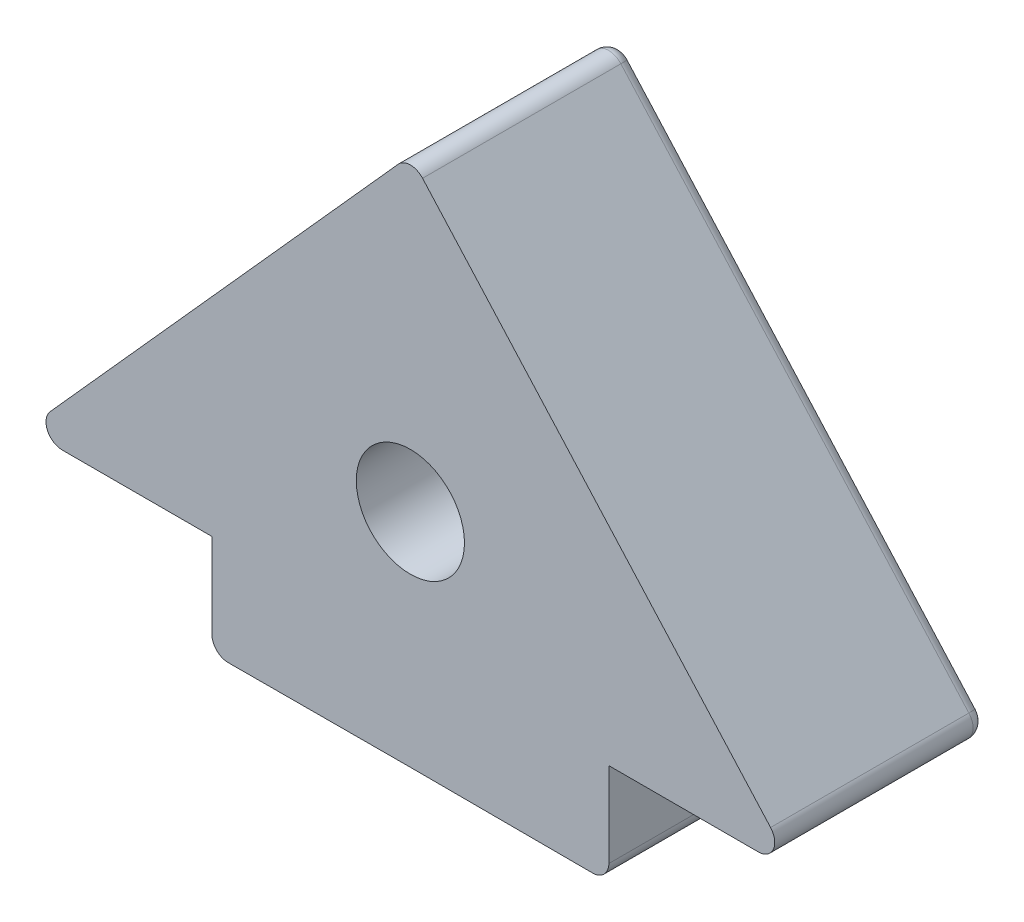
SolidWorks part; units mm, degrees
ref_plane "前视基准面" through (0, 0, 0) normal (0, 0, 1) x (1, 0, 0)
ref_plane "上视基准面" through (0, 0, 0) normal (0, 1, 0) x (1, 0, 0)
ref_plane "右视基准面" through (0, 0, 0) normal (1, 0, 0) x (0, 0, -1)
sketch "草图1" plane through (0, 0, 0) normal (0, 0, 1) x (1, 0, 0)
  line L0 (-0.7032, 8.7731) -> (-12.2849, -4.1469) construction
  line L1 (-11.5817, -5.7217) -> (-7.0052, -5.7217) construction
  line L2 (-7.0052, -5.7217) -> (-7.0052, -8.1427) construction
  line L3 (-6.0585, -9.0871) -> (0, -9.0721) construction
  line L4 (6.0585, -9.0871) -> (0, -9.0721) construction
  line L5 (7.0052, -5.7217) -> (7.0052, -8.1427) construction
  line L6 (11.5817, -5.7217) -> (7.0052, -5.7217) construction
  line L7 (0.7032, 8.7731) -> (12.2849, -4.1469) construction
  line L8 (-0.4054, 8.5061) -> (-11.9871, -4.4139)
  line L9 (-11.5817, -5.3217) -> (-6.6052, -5.3217)
  line L10 (-6.6052, -5.3217) -> (-6.6052, -8.1427)
  line L11 (-6.0595, -8.6871) -> (0, -8.6721)
  line L12 (6.0595, -8.6871) -> (0, -8.6721)
  line L13 (6.6052, -5.3217) -> (6.6052, -8.1427)
  line L14 (11.5817, -5.3217) -> (6.6052, -5.3217)
  line L15 (0.4054, 8.5061) -> (11.9871, -4.4139)
  line L16 (-0.7032, 8.7731) -> (-12.2849, -4.1469) construction
  line L17 (-11.5817, -5.7217) -> (-7.0052, -5.7217) construction
  line L18 (-7.0052, -5.7217) -> (-7.0052, -8.1427) construction
  line L19 (-6.0585, -9.0871) -> (0, -9.0721) construction
  line L20 (6.0585, -9.0871) -> (0, -9.0721) construction
  line L21 (7.0052, -5.7217) -> (7.0052, -8.1427) construction
  line L22 (11.5817, -5.7217) -> (7.0052, -5.7217) construction
  line L23 (0.7032, 8.7731) -> (12.2849, -4.1469) construction
  arc A0 (-12.2849, -4.1469) -> (-11.5817, -5.7217) centre (-11.5817, -4.7773) ccw construction
  arc A1 (-7.0052, -8.1427) -> (-6.0585, -9.0871) centre (-6.0608, -8.1427) ccw construction
  arc A2 (6.0585, -9.0871) -> (7.0052, -8.1427) centre (6.0608, -8.1427) ccw construction
  arc A3 (11.5817, -5.7217) -> (12.2849, -4.1469) centre (11.5817, -4.7773) ccw construction
  arc A4 (0.7032, 8.7731) -> (-0.7032, 8.7731) centre (0, 8.1427) ccw construction
  arc A5 (-11.9871, -4.4139) -> (-11.5817, -5.3217) centre (-11.5817, -4.7773) ccw
  arc A6 (-6.6052, -8.1427) -> (-6.0595, -8.6871) centre (-6.0608, -8.1427) ccw
  arc A7 (6.0595, -8.6871) -> (6.6052, -8.1427) centre (6.0608, -8.1427) ccw
  arc A8 (11.5817, -5.3217) -> (11.9871, -4.4139) centre (11.5817, -4.7773) ccw
  arc A9 (0.4054, 8.5061) -> (-0.4054, 8.5061) centre (0, 8.1427) ccw
  circle A10 centre (0, -1.3083) radius 7.2 construction
  arc A11 (-12.2849, -4.1469) -> (-11.5817, -5.7217) centre (-11.5817, -4.7773) ccw construction
  arc A12 (-7.0052, -8.1427) -> (-6.0585, -9.0871) centre (-6.0608, -8.1427) ccw construction
  arc A13 (6.0585, -9.0871) -> (7.0052, -8.1427) centre (6.0608, -8.1427) ccw construction
  arc A14 (11.5817, -5.7217) -> (12.2849, -4.1469) centre (11.5817, -4.7773) ccw construction
  arc A15 (0.7032, 8.7731) -> (-0.7032, 8.7731) centre (0, 8.1427) ccw construction
  circle A16 centre (0, -1.3083) radius 1.8
  dimension "D2" = 3.6
  dimension "D1" = 0.4
extrude "凸台-拉伸1" add sketch "草图1" along normal blind 7
sketch "草图2" plane through (0, 0, 0) normal (0, 0, -1) x (-1, 0, 0)
  circle A0 centre (0, -1.3083) radius 1.8
extrude "凸台-拉伸2" add sketch "草图2" against normal blind 2
fillet "圆角1" radius 0.4 13 edges at (-6.4453, -8.5282, 0) (6.4453, -8.5282, 0) (12.0788, -4.9993, 0) (-12.0788, -4.9993, 0) (0, 8.6872, 0) (-6.6052, -6.7322, 0) (9.0934, -5.3217, 0) (-9.0934, -5.3217, 0) (-3.0297, -8.6796, 0) (3.0297, -8.6796, 0) (6.6052, -6.7322, 0) (-6.1962, 2.0461, 0) (6.1962, 2.0461, 0)
